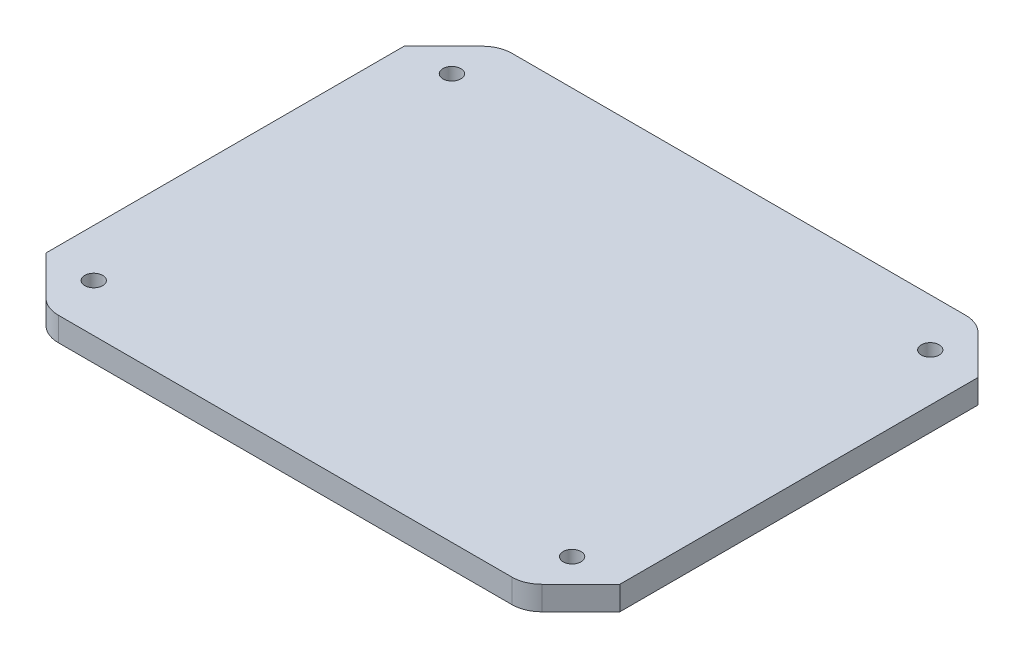
SolidWorks part; units mm, degrees
ref_plane "Front Plane" through (0, 0, 0) normal (0, 0, 1) x (1, 0, 0)
ref_plane "Top Plane" through (0, 0, 0) normal (0, 1, 0) x (1, 0, 0)
ref_plane "Right Plane" through (0, 0, 0) normal (1, 0, 0) x (0, 0, -1)
sketch "Sketch1" plane through (0, 0, 0) normal (0, 1, 0) x (1, 0, 0)
  line L0 (-40.2452, 36.7506) -> (-46.7808, 30.215)
  line L1 (-46.7808, 30.215) -> (-46.7808, -29.785)
  line L2 (-46.7808, -29.785) -> (-40.2452, -36.3205)
  line L3 (-36.7097, -37.785) -> (39.2903, -37.785)
  line L4 (42.8258, -36.3205) -> (49.3614, -29.785)
  line L5 (49.3614, -29.785) -> (49.3614, 30.215)
  line L6 (49.3614, 30.215) -> (42.8258, 36.7506)
  line L7 (39.2903, 38.215) -> (-36.7097, 38.215)
  arc A0 (-40.2452, -36.3205) -> (-36.7097, -37.785) centre (-36.7097, -32.785) ccw
  arc A1 (39.2903, -37.785) -> (42.8258, -36.3205) centre (39.2903, -32.785) ccw
  arc A2 (42.8258, 36.7506) -> (39.2903, 38.215) centre (39.2903, 33.215) ccw
  arc A3 (-36.7097, 38.215) -> (-40.2452, 36.7506) centre (-36.7097, 33.215) ccw
  circle A4 centre (41.3614, -29.785) radius 1.5
  circle A5 centre (41.3614, 30.215) radius 1.5
  circle A6 centre (-38.7808, -29.785) radius 1.5
  circle A7 centre (-38.7808, 30.215) radius 1.5
extrude "Boss-Extrude1" add sketch "Sketch1" along normal blind 4
